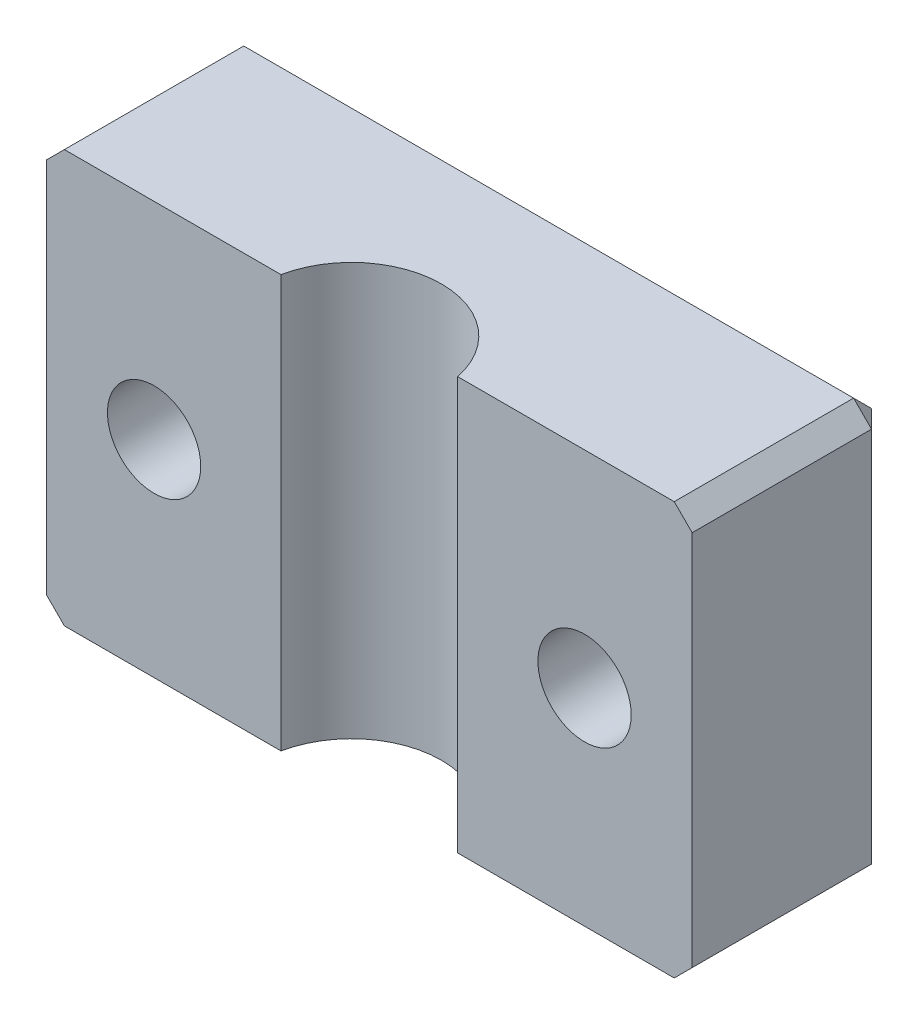
SolidWorks part; units mm, degrees
material "ABS"
ref_plane "Front Plane" through (0, 0, 0) normal (0, 0, 1) x (1, 0, 0)
ref_plane "Top Plane" through (0, 0, 0) normal (0, 1, 0) x (1, 0, 0)
ref_plane "Right Plane" through (0, 0, 0) normal (1, 0, 0) x (0, 0, -1)
sketch "Sketch1" plane through (0, 0, 0) normal (0, 1, 0) x (1, 0, 0)
  line L0 (-18, 0) -> (18, 0)
  line L1 (18, 0) -> (18, -11)
  line L2 (18, -11) -> (4.9245, -11)
  line L3 (-18, -11) -> (-18, 0)
  line L4 (0, 0) -> (0, -10) construction
  line L5 (-4.9245, -11) -> (-18, -11)
  arc A0 (4.9245, -11) -> (-4.9245, -11) centre (0, -12) ccw
  dimension "D2" = 1
  dimension "D3" = 10.05
  dimension "D1" = 36
  dimension "D4" = 11
extrude "Boss-Extrude1" add sketch "Sketch1" along normal blind 23
sketch "Sketch2" plane through (0, 0, 11) normal (0, 0, 1) x (1, 0, 0)
  line L0 (0, 23) -> (0, 0) construction
  line L1 (4.9245, 23) -> (-4.9245, 23) construction
  line L2 (-18, 11.5) -> (18, 11.5) construction
  line L3 (-18, 23) -> (-18, 0) construction
  line L4 (18, 23) -> (18, 0) construction
  circle A0 centre (-12, 11.5) radius 2.6
  circle A1 centre (12, 11.5) radius 2.6
  dimension "D1" = 5.2
  dimension "D2" = 12
extrude "Cut-Extrude1" cut sketch "Sketch2" against normal up to next
chamfer "Chamfer1" distance 1 angle 45 8 edges at (18, 0, 5.5) (-18, 0, 5.5) (-18, 23, 5.5) (18, 23, 5.5) (-18, 11.5, 0) (0, 0, 0) (18, 11.5, 0) (0, 23, 0)
